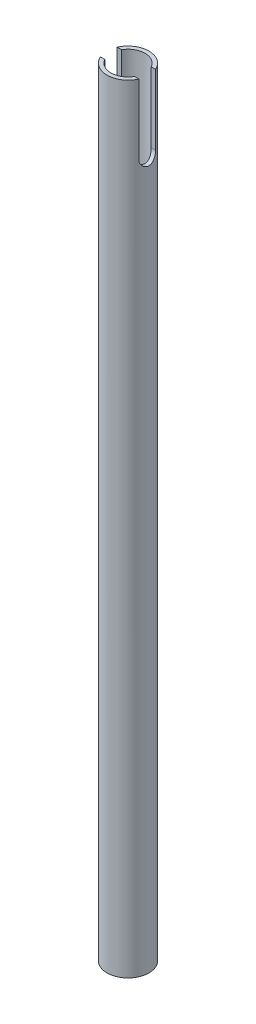
SolidWorks part; units mm, degrees
material "AISI 4130 Steel, annealed at 865C"
ref_plane "X-Y Datum" through (0, 0, 0) normal (0, 0, 1) x (1, 0, 0)
ref_plane "X-Z Datum" through (0, 0, 0) normal (0, 1, 0) x (1, 0, 0)
ref_plane "Y-Z Datum" through (0, 0, 0) normal (1, 0, 0) x (0, 0, -1)
sketch "Sketch1" plane through (0, 0, 0) normal (0, 1, 0) x (1, 0, 0)
  circle A0 centre (0, 0) radius 7.9375
  circle A1 centre (0, 0) radius 6.4643
  dimension "D1" = 15.875
  dimension "D2" = 1.4732
extrude "Boss-Extrude1" add sketch "Sketch1" along normal offset from surface (294.8389 mm away) 25.4
sketch "Sketch4" plane through (0, 0, 0) normal (1, 0, 0) x (0, 0, -1)
  line L5 (0, 319.0837) -> (0, 268.2837) construction
  line L7 (3.175, 319.0837) -> (3.175, 268.2837)
  line L8 (-3.175, 319.0837) -> (-3.175, 268.2837)
  arc A0 (3.175, 319.0837) -> (-3.175, 319.0837) centre (0, 319.0837) ccw
  arc A1 (-3.175, 268.2837) -> (3.175, 268.2837) centre (0, 268.2837) ccw
  point P4 (0, 293.6837)
  dimension "D1" = 6.35
  dimension "D2" = 25.4
extrude "Cut-Extrude1" cut sketch "Sketch4" against normal through all both and the other way through all
